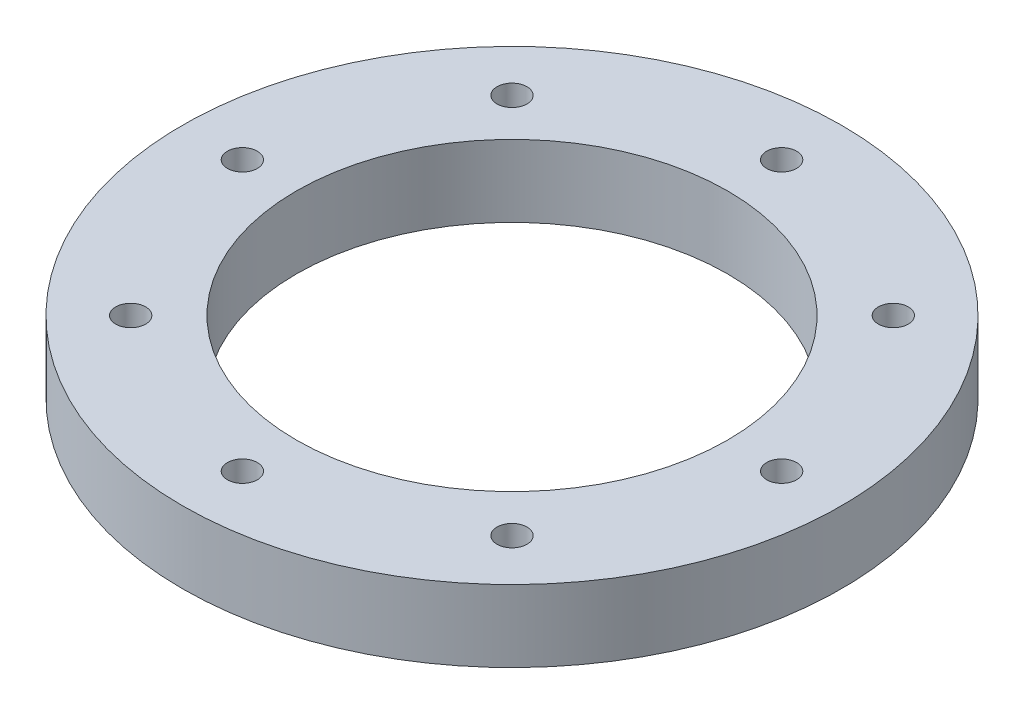
SolidWorks part; units mm, degrees
material "ESUN PLA +"
ref_plane "Front Plane" through (0, 0, 0) normal (0, 0, 1) x (1, 0, 0)
ref_plane "Top Plane" through (0, 0, 0) normal (0, 1, 0) x (1, 0, 0)
ref_plane "Right Plane" through (0, 0, 0) normal (1, 0, 0) x (0, 0, -1)
sketch "Sketch1" plane through (0, 0, 0) normal (0, 1, 0) x (1, 0, 0)
  circle A0 centre (0, 0) radius 36
  circle A1 centre (0, 0) radius 55
  dimension "D1" = 72
  dimension "D2" = 110
extrude "Boss-Extrude1" add sketch "Sketch1" along normal blind 12
sketch "Sketch2" plane through (0, 12, 0) normal (0, 1, 0) x (1, 0, 0)
  circle A0 centre (0, 0) radius 45 construction
  circle A1 centre (45, 0) radius 1.7
  dimension "D1" = 90
  dimension "D2" = 3.4
extrude "Cut-Extrude1" cut sketch "Sketch2" against normal through all both and the other way through all
sketch "Sketch3" plane through (0, 12, 0) normal (0, 1, 0) x (1, 0, 0)
  circle A0 centre (45, 0) radius 2.5
  dimension "D1" = 5
extrude "Cut-Extrude2" cut sketch "Sketch3" against normal blind 5
pattern_circular "CirPattern1" count 8 over 360 about axis through (0, 0, 0) along (0, 1, 0) of "Cut-Extrude1", "Cut-Extrude2"
